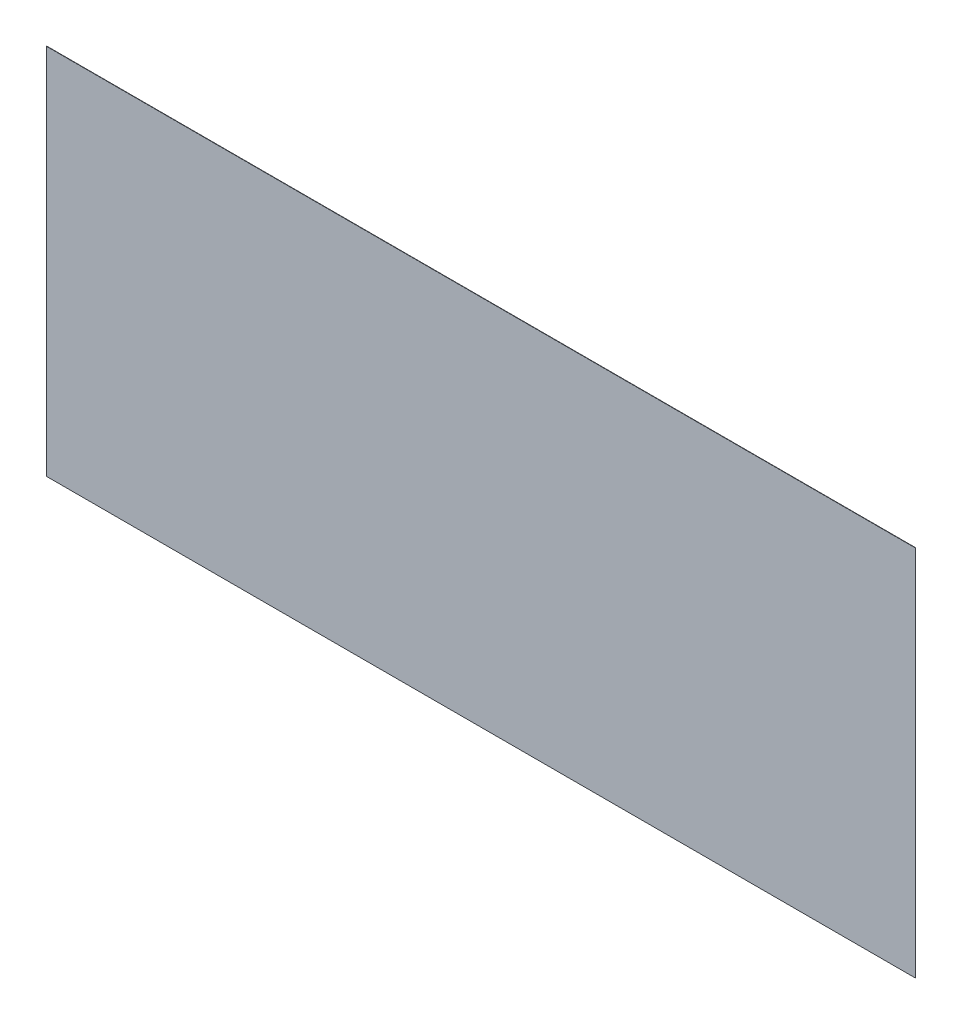
SolidWorks part; units mm, degrees
material "PVC 0.007 Plasticized"
ref_plane "Front Plane" through (0, 0, 0) normal (0, 0, 1) x (1, 0, 0)
ref_plane "Top Plane" through (0, 0, 0) normal (0, 1, 0) x (1, 0, 0)
ref_plane "Right Plane" through (0, 0, 0) normal (1, 0, 0) x (0, 0, -1)
sketch "Sketch1" plane through (0, 0, 0) normal (0, 0, 1) x (1, 0, 0)
  line L1 (-1050, -450) -> (1050, -450)
  line L2 (-1050, -450) -> (-1050, 450)
  line L3 (-1050, 450) -> (1050, 450)
  line L4 (1050, -450) -> (1050, 450)
  line L5 (-1050, -450) -> (1050, 450) construction
  line L6 (-1050, 450) -> (1050, -450) construction
  point P0 (0, 0)
  dimension "D1" = 2100
  dimension "D2" = 900
extrude "Boss-Extrude1" add sketch "Sketch1" along normal blind 0.9
shell "Shell1" thickness 0.35
